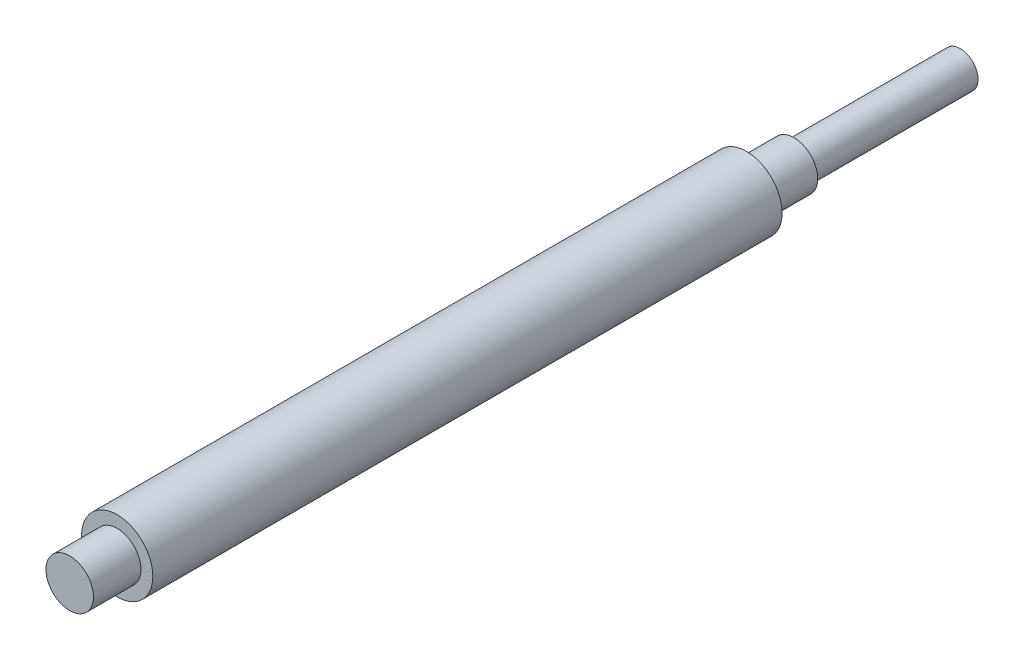
SolidWorks part; units mm, degrees
material "Aço inoxidável (ferrítico)"
ref_plane "Plano frontal" through (0, 0, 0) normal (0, 0, 1) x (1, 0, 0)
ref_plane "Plano superior" through (0, 0, 0) normal (0, 1, 0) x (1, 0, 0)
ref_plane "Plano direito" through (0, 0, 0) normal (1, 0, 0) x (0, 0, -1)
sketch "Esboço1" plane through (0, 0, 0) normal (0, 0, 1) x (1, 0, 0)
  circle A0 centre (0, 0) radius 3
  dimension "D1" = 6
extrude "Ressalto-extrusão1" add sketch "Esboço1" along normal blind 75
sketch "Esboço2" plane through (0, 0, 75) normal (0, 0, 1) x (1, 0, 0)
  circle A0 centre (0, 0) radius 3
  circle A1 centre (0, 0) radius 2
  dimension "D1" = 6
  dimension "D2" = 4
extrude "Corte-extrusão1" cut sketch "Esboço2" against normal blind 4
sketch "Esboço3" plane through (0, 0, 0) normal (0, 0, -1) x (-1, 0, 0)
  circle A0 centre (0, 0) radius 3
  circle A1 centre (0, 0) radius 2
  dimension "D1" = 6
  dimension "D2" = 4
extrude "Corte-extrusão2" cut sketch "Esboço3" against normal offset from surface (18 mm away) 53 up to face at (2, 0, 71)
sketch "Esboço4" plane through (0, 0, 0) normal (0, 0, -1) x (-1, 0, 0)
  circle A0 centre (0, 0) radius 2.5
  circle A1 centre (0, 0) radius 1.5
  dimension "D1" = 5
  dimension "D2" = 3
extrude "Corte-extrusão3" cut sketch "Esboço4" against normal offset from surface (14 mm away) 4 up to face at (3, 0, 18)
